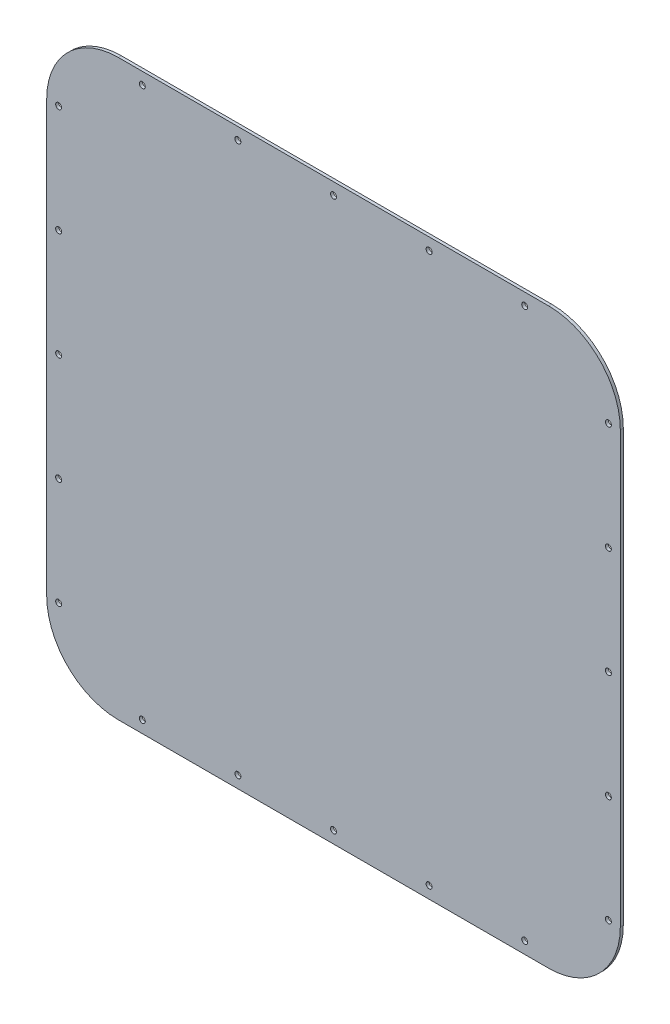
SolidWorks part; units mm, degrees
ref_plane "Front Plane" through (0, 0, 0) normal (0, 0, 1) x (1, 0, 0)
ref_plane "Top Plane" through (0, 0, 0) normal (0, 1, 0) x (1, 0, 0)
ref_plane "Right Plane" through (0, 0, 0) normal (1, 0, 0) x (0, 0, -1)
sketch "Model" plane through (0, 0, 0) normal (0, 0, 1) x (1, 0, 0)
  line L23 (-152.4, -939.8) -> (-609.6, -939.8)
  line L24 (-685.8, -1016) -> (-685.8, -1473.2)
  line L25 (-609.6, -1549.4) -> (-152.4, -1549.4)
  line L26 (-76.2, -1473.2) -> (-76.2, -1016)
  circle A0 centre (-381, -952.5) radius 3.175
  circle A1 centre (-88.9, -1473.4329) radius 3.175
  circle A2 centre (-88.9, -1359.1329) radius 3.175
  circle A3 centre (-88.9, -1244.8329) radius 3.175
  circle A4 centre (-88.9, -1130.5329) radius 3.175
  circle A5 centre (-482.6, -1536.7) radius 3.175
  circle A6 centre (-584.2, -1536.7) radius 3.175
  circle A7 centre (-673.1, -1244.8329) radius 3.175
  circle A8 centre (-279.4, -952.5) radius 3.175
  circle A9 centre (-482.6, -952.5) radius 3.175
  circle A10 centre (-584.2, -952.5) radius 3.175
  circle A11 centre (-177.8, -952.5) radius 3.175
  circle A12 centre (-88.9, -1016.2329) radius 3.175
  circle A13 centre (-673.1, -1016.2329) radius 3.175
  circle A14 centre (-673.1, -1130.5329) radius 3.175
  circle A15 centre (-673.1, -1473.4329) radius 3.175
  circle A16 centre (-381, -1536.7) radius 3.175
  circle A17 centre (-279.4, -1536.7) radius 3.175
  circle A18 centre (-177.8, -1536.7) radius 3.175
  circle A19 centre (-673.1, -1359.1329) radius 3.175
  arc A20 (-76.2, -1016) -> (-152.4, -939.8) centre (-152.4, -1016) ccw
  arc A21 (-609.6, -939.8) -> (-685.8, -1016) centre (-609.6, -1016) ccw
  arc A22 (-685.8, -1473.2) -> (-609.6, -1549.4) centre (-609.6, -1473.2) ccw
  arc A23 (-152.4, -1549.4) -> (-76.2, -1473.2) centre (-152.4, -1473.2) ccw
extrude "Boss-Extrude1" add sketch "Model" along normal blind 3.175
